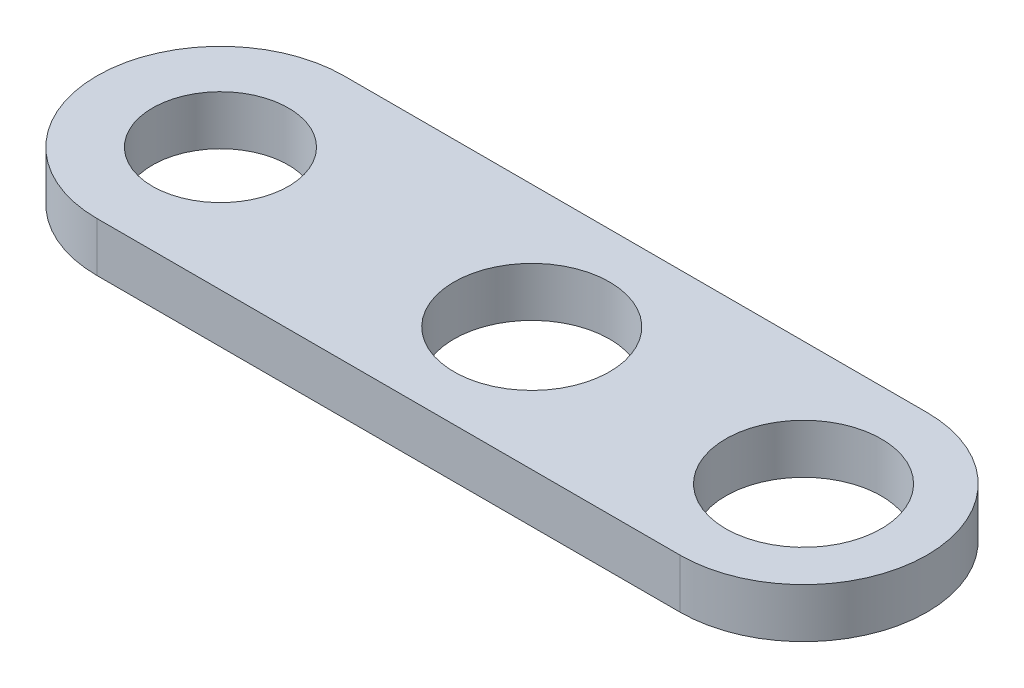
SolidWorks part; units mm, degrees
material "Copper"
ref_plane "Front Plane" through (0, 0, 0) normal (0, 0, 1) x (1, 0, 0)
ref_plane "Top Plane" through (0, 0, 0) normal (0, 1, 0) x (1, 0, 0)
ref_plane "Right Plane" through (0, 0, 0) normal (1, 0, 0) x (0, 0, -1)
sketch "Sketch2" plane through (0, 0, 0) normal (0, 1, 0) x (1, 0, 0)
  line L0 (9.45, 0) -> (23.6, 0) construction
  line L1 (23.6, 5) -> (0, 5)
  line L3 (0, -5) -> (23.6, -5)
  circle A1 centre (23.6, 0) radius 3.15
  circle A2 centre (12.6, 0) radius 3.15
  arc A3 (23.6, -5) -> (23.6, 5) centre (23.6, 0) ccw
  circle A7 centre (0, 0) radius 2.75
  arc A8 (0, 5) -> (0, -5) centre (0, 0) ccw
  point P4 (12.6, 0)
  point P13 (8, -83.1034)
  dimension "D1" = 6.3
  dimension "D2" = 5
  dimension "D3" = 12.6
  dimension "D7" = 5
  dimension "D10" = 5.5
  dimension "D5" = 11
extrude "Boss-Extrude1" add sketch "Sketch2" against normal blind 2
